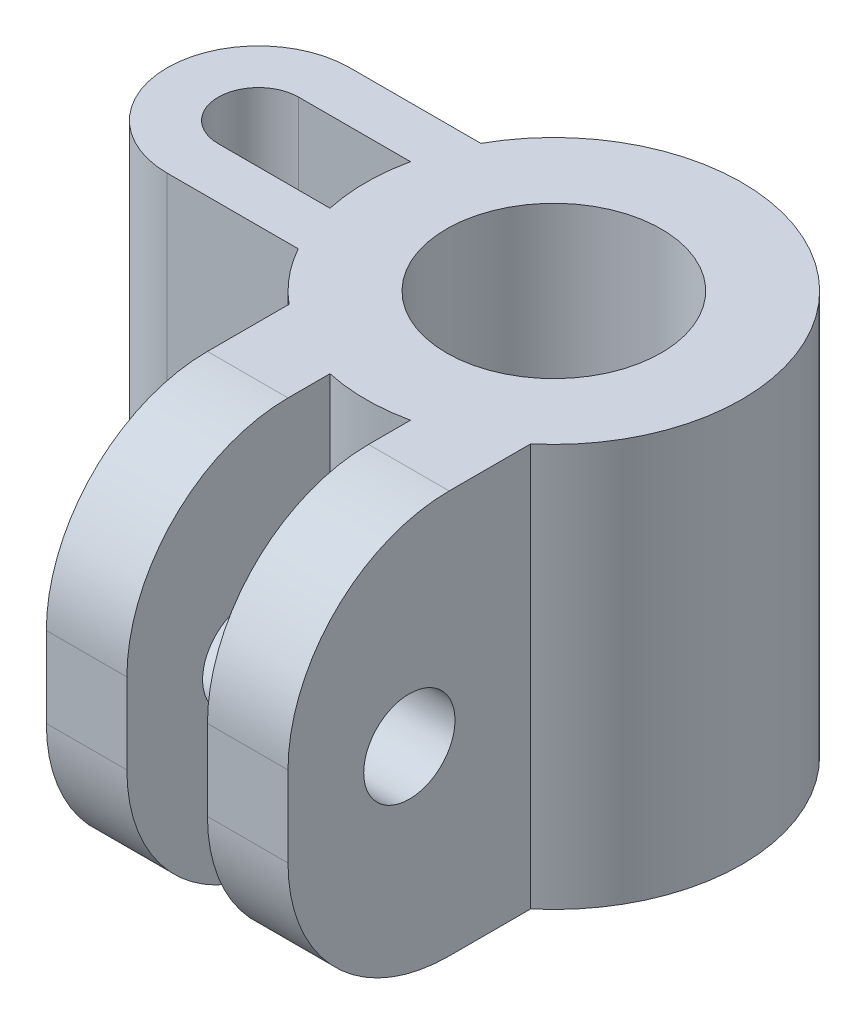
SolidWorks part; units mm, degrees
ref_plane "Front Plane" through (0, 0, 0) normal (0, 0, 1) x (1, 0, 0)
ref_plane "Top Plane" through (0, 0, 0) normal (0, 1, 0) x (1, 0, 0)
ref_plane "Right Plane" through (0, 0, 0) normal (1, 0, 0) x (0, 0, -1)
sketch "Sketch1" plane through (0, 0, 0) normal (0, 1, 0) x (1, 0, 0)
  line L0 (-35, 0) -> (35, 0) construction
  line L1 (-55, -17) -> (-30.5941, -17)
  line L2 (-30.5941, 17) -> (-55, 17)
  line L3 (-55, 7.5) -> (-34.187, 7.5)
  line L4 (-55, -7.5) -> (-34.187, -7.5)
  line L5 (0, 0) -> (0, -55) construction
  line L6 (-34.187, -55) -> (52.7702, -55) construction
  line L7 (7.5, -34.187) -> (7.5, -72)
  line L8 (7.5, -72) -> (22.5, -72)
  line L9 (22.5, -72) -> (22.5, -26.8095)
  line L10 (-22.5, -72) -> (-22.5, -26.8095)
  line L11 (-7.5, -72) -> (-22.5, -72)
  line L12 (-7.5, -34.187) -> (-7.5, -72)
  circle A0 centre (0, 0) radius 35
  circle A1 centre (0, 0) radius 20
  arc A2 (-55, 17) -> (-55, -17) centre (-55, 0) ccw
  arc A3 (-55, 7.5) -> (-55, -7.5) centre (-55, 0) ccw
  dimension "D1" = 70
  dimension "D2" = 40
  dimension "D3" = 17
  dimension "D4" = 7.5
  dimension "D5" = 55
  dimension "D6" = 15
  dimension "D7" = 17
  dimension "15" = 15
  dimension "D8" = 55
extrude "Boss-Extrude2" add sketch "Sketch1" along normal blind 75 contours A0 A1 | A3 L3 A0 L2 A2 L1 L4 | A0 L10 L11 L12 | A0 L7 L8 L9
sketch "Sketch2" plane through (22.5, 0, 0) normal (1, 0, 0) x (0, 0, -1)
  line L0 (-72, 75) -> (-26.8095, 75) construction
  line L4 (-72, 75) -> (-72, 0) construction
  circle A0 centre (-49.405, 37.5) radius 8.5
  point P6 (0, 0)
  point P8 (0, 0)
  dimension "D3" = 17
  dimension "D1" = 37.5
  dimension "D2" = 22.595
extrude "Cut-Extrude1" cut sketch "Sketch2" against normal up to surface and the other way through all contours A0 up to face at (-22.5, 37.5, 49.4048)
fillet "Fillet1" radius 30 4 edges at (-15, 0, 72) (-15, 75, 72) (15, 0, 72) (15, 75, 72)
